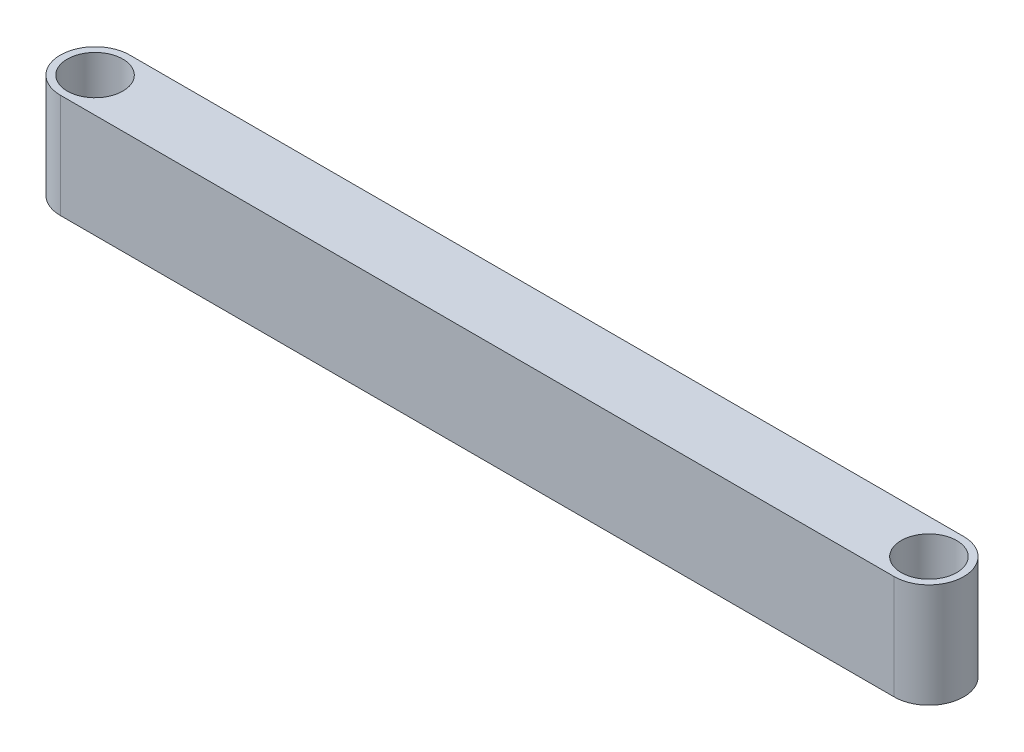
SolidWorks part; units mm, degrees
ref_plane "Front Plane" through (0, 0, 0) normal (0, 0, 1) x (1, 0, 0)
ref_plane "Top Plane" through (0, 0, 0) normal (0, 1, 0) x (1, 0, 0)
ref_plane "Right Plane" through (0, 0, 0) normal (1, 0, 0) x (0, 0, -1)
sketch "Sketch1" plane through (0, 0, 0) normal (0, 1, 0) x (1, 0, 0)
  line L0 (-56.2744, 11.7175) -> (-44.2744, 11.7175) construction
  line L1 (-56.2744, 12.2175) -> (-44.2744, 12.2175)
  line L2 (-56.2744, 11.2175) -> (-44.2744, 11.2175)
  arc A0 (-56.2744, 12.2175) -> (-56.2744, 11.2175) centre (-56.2744, 11.7175) ccw
  arc A1 (-44.2744, 11.2175) -> (-44.2744, 12.2175) centre (-44.2744, 11.7175) ccw
  circle A2 centre (-56.2744, 11.7175) radius 0.4
  circle A3 centre (-44.2744, 11.7175) radius 0.4
  point P2 (-50.2744, 11.7175)
extrude "Boss-Extrude1" add sketch "Sketch1" along normal blind 1.5
